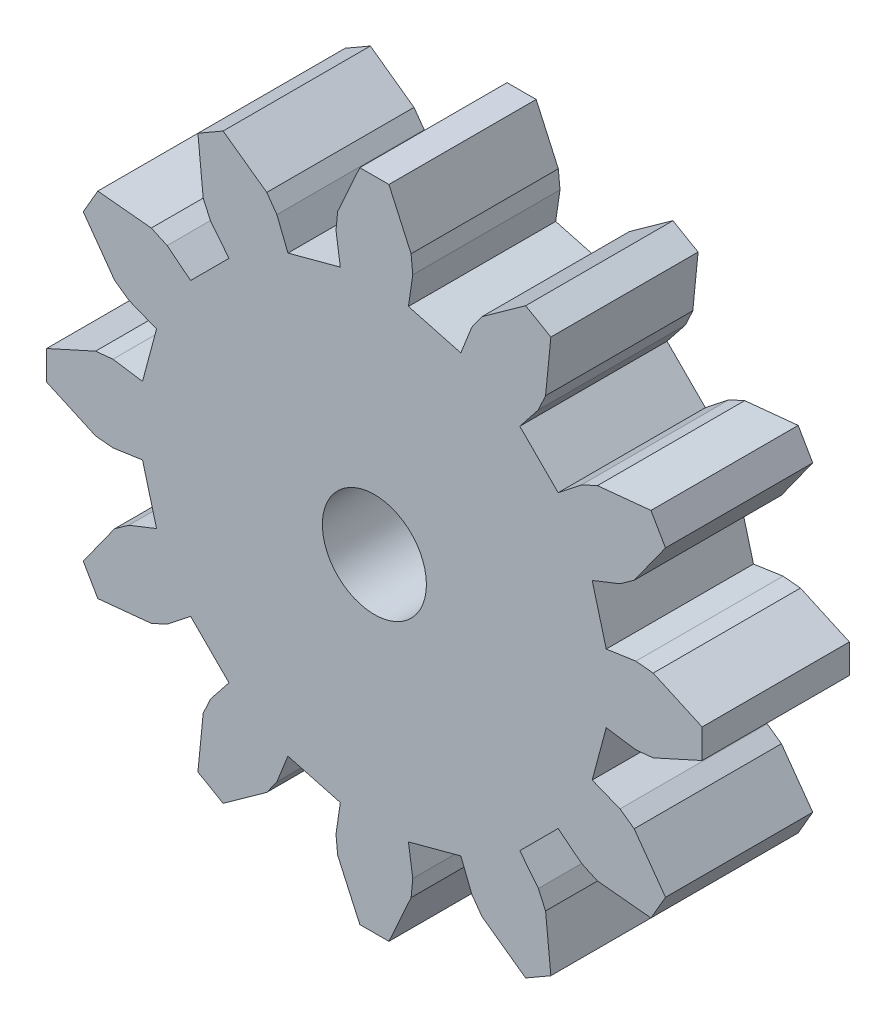
SolidWorks part; units mm, degrees
ref_plane "Front Plane" through (0, 0, 0) normal (0, 0, 1) x (1, 0, 0)
ref_plane "Top Plane" through (0, 0, 0) normal (0, 1, 0) x (1, 0, 0)
ref_plane "Right Plane" through (0, 0, 0) normal (1, 0, 0) x (0, 0, -1)
sketch "Model" plane through (0, 0, 0) normal (0, 0, 1) x (1, 0, 0)
  line L0 (85.0385, 125.8427) -> (85.6414, 125.9312)
  line L1 (85.6414, 125.9312) -> (85.995, 125.8968)
  line L2 (85.995, 125.8968) -> (86.9924, 125.4453)
  line L3 (86.9924, 125.4453) -> (86.9924, 124.8526)
  line L4 (86.9924, 124.8526) -> (85.995, 124.4011)
  line L5 (85.995, 124.4011) -> (85.6414, 124.3667)
  line L6 (85.6414, 124.3667) -> (85.0385, 124.4553)
  line L7 (85.0385, 124.4553) -> (84.7524, 123.3877)
  line L8 (84.7524, 123.3877) -> (85.3188, 123.1629)
  line L9 (85.3188, 123.1629) -> (85.6079, 122.9564)
  line L10 (85.6079, 122.9564) -> (86.2459, 122.0667)
  line L11 (86.2459, 122.0667) -> (85.9496, 121.5533)
  line L12 (85.9496, 121.5533) -> (84.8601, 121.661)
  line L13 (84.8601, 121.661) -> (84.5366, 121.8081)
  line L14 (84.5366, 121.8081) -> (84.0587, 122.1862)
  line L15 (84.0587, 122.1862) -> (83.2772, 121.4047)
  line L16 (83.2772, 121.4047) -> (83.6554, 120.9268)
  line L17 (83.6554, 120.9268) -> (83.8024, 120.6034)
  line L18 (83.8024, 120.6034) -> (83.9101, 119.5139)
  line L19 (83.9101, 119.5139) -> (83.3968, 119.2175)
  line L20 (83.3968, 119.2175) -> (82.5071, 119.8555)
  line L21 (82.5071, 119.8555) -> (82.3005, 120.1446)
  line L22 (82.3005, 120.1446) -> (82.0757, 120.711)
  line L23 (82.0757, 120.711) -> (81.0082, 120.425)
  line L24 (81.0082, 120.425) -> (81.0967, 119.822)
  line L25 (81.0967, 119.822) -> (81.0624, 119.4684)
  line L26 (81.0624, 119.4684) -> (80.6108, 118.471)
  line L27 (80.6108, 118.471) -> (80.0181, 118.471)
  line L28 (80.0181, 118.471) -> (79.5666, 119.4684)
  line L29 (79.5666, 119.4684) -> (79.5322, 119.822)
  line L30 (79.5322, 119.822) -> (79.6208, 120.425)
  line L31 (79.6208, 120.425) -> (78.5533, 120.711)
  line L32 (78.5533, 120.711) -> (78.3285, 120.1446)
  line L33 (78.3285, 120.1446) -> (78.1219, 119.8555)
  line L34 (78.1219, 119.8555) -> (77.2322, 119.2175)
  line L35 (77.2322, 119.2175) -> (76.7189, 119.5139)
  line L36 (76.7189, 119.5139) -> (76.8265, 120.6034)
  line L37 (76.8265, 120.6034) -> (76.9736, 120.9268)
  line L38 (76.9736, 120.9268) -> (77.3517, 121.4047)
  line L39 (77.3517, 121.4047) -> (76.5702, 122.1862)
  line L40 (76.5702, 122.1862) -> (76.0924, 121.8081)
  line L41 (76.0924, 121.8081) -> (75.7689, 121.661)
  line L42 (75.7689, 121.661) -> (74.6794, 121.5533)
  line L43 (74.6794, 121.5533) -> (74.3831, 122.0666)
  line L44 (74.3831, 122.0666) -> (75.0211, 122.9564)
  line L45 (75.0211, 122.9564) -> (75.3101, 123.1629)
  line L46 (75.3101, 123.1629) -> (75.8765, 123.3877)
  line L47 (75.8765, 123.3877) -> (75.5905, 124.4553)
  line L48 (75.5905, 124.4553) -> (74.9876, 124.3667)
  line L49 (74.9876, 124.3667) -> (74.6339, 124.4011)
  line L50 (74.6339, 124.4011) -> (73.6366, 124.8526)
  line L51 (73.6366, 124.8526) -> (73.6366, 125.4453)
  line L52 (73.6366, 125.4453) -> (74.6339, 125.8968)
  line L53 (74.6339, 125.8968) -> (74.9876, 125.9312)
  line L54 (74.9876, 125.9312) -> (75.5905, 125.8427)
  line L55 (75.5905, 125.8427) -> (75.8766, 126.9102)
  line L56 (75.8766, 126.9102) -> (75.3101, 127.135)
  line L57 (75.3101, 127.135) -> (75.0211, 127.3416)
  line L58 (75.0211, 127.3416) -> (74.3831, 128.2313)
  line L59 (74.3831, 128.2313) -> (74.6794, 128.7446)
  line L60 (74.6794, 128.7446) -> (75.7689, 128.6369)
  line L61 (75.7689, 128.6369) -> (76.0924, 128.4899)
  line L62 (76.0924, 128.4899) -> (76.5703, 128.1117)
  line L63 (76.5703, 128.1117) -> (77.3517, 128.8932)
  line L64 (77.3517, 128.8932) -> (76.9736, 129.3711)
  line L65 (76.9736, 129.3711) -> (76.8265, 129.6945)
  line L66 (76.8265, 129.6945) -> (76.7189, 130.784)
  line L67 (76.7189, 130.784) -> (77.2322, 131.0804)
  line L68 (77.2322, 131.0804) -> (78.1219, 130.4424)
  line L69 (78.1219, 130.4424) -> (78.3285, 130.1533)
  line L70 (78.3285, 130.1533) -> (78.5533, 129.5869)
  line L71 (78.5533, 129.5869) -> (79.6208, 129.873)
  line L72 (79.6208, 129.873) -> (79.5323, 130.4759)
  line L73 (79.5323, 130.4759) -> (79.5666, 130.8295)
  line L74 (79.5666, 130.8295) -> (80.0181, 131.8269)
  line L75 (80.0181, 131.8269) -> (80.6109, 131.8269)
  line L76 (80.6109, 131.8269) -> (81.0624, 130.8295)
  line L77 (81.0624, 130.8295) -> (81.0967, 130.4759)
  line L78 (81.0967, 130.4759) -> (81.0082, 129.873)
  line L79 (81.0082, 129.873) -> (82.0757, 129.5869)
  line L80 (82.0757, 129.5869) -> (82.3005, 130.1533)
  line L81 (82.3005, 130.1533) -> (82.5071, 130.4424)
  line L82 (82.5071, 130.4424) -> (83.3968, 131.0804)
  line L83 (83.3968, 131.0804) -> (83.9101, 130.784)
  line L84 (83.9101, 130.784) -> (83.8024, 129.6945)
  line L85 (83.8024, 129.6945) -> (83.6554, 129.3711)
  line L86 (83.6554, 129.3711) -> (83.2773, 128.8932)
  line L87 (83.2773, 128.8932) -> (84.0587, 128.1117)
  line L88 (84.0587, 128.1117) -> (84.5366, 128.4899)
  line L89 (84.5366, 128.4899) -> (84.8601, 128.6369)
  line L90 (84.8601, 128.6369) -> (85.9496, 128.7446)
  line L91 (85.9496, 128.7446) -> (86.2459, 128.2313)
  line L92 (86.2459, 128.2313) -> (85.6079, 127.3416)
  line L93 (85.6079, 127.3416) -> (85.3189, 127.135)
  line L94 (85.3189, 127.135) -> (84.7524, 126.9102)
  line L95 (84.7524, 126.9102) -> (85.0385, 125.8427)
extrude "Boss-Extrude1" add sketch "Model" along normal blind 3
sketch "Sketch2" plane through (0, 0, 3) normal (0, 0, 1) x (1, 0, 0)
  line L0 (75.7335, 123.9215) -> (84.8955, 126.3764) construction
  line L1 (75.5905, 124.4553) -> (75.8765, 123.3877) construction
  line L2 (85.0385, 125.8427) -> (84.7524, 126.9102) construction
  circle A0 centre (80.3145, 125.149) radius 1.06
  dimension "D1" = 2.12
extrude "Cut-Extrude1" cut sketch "Sketch2" against normal blind 3
